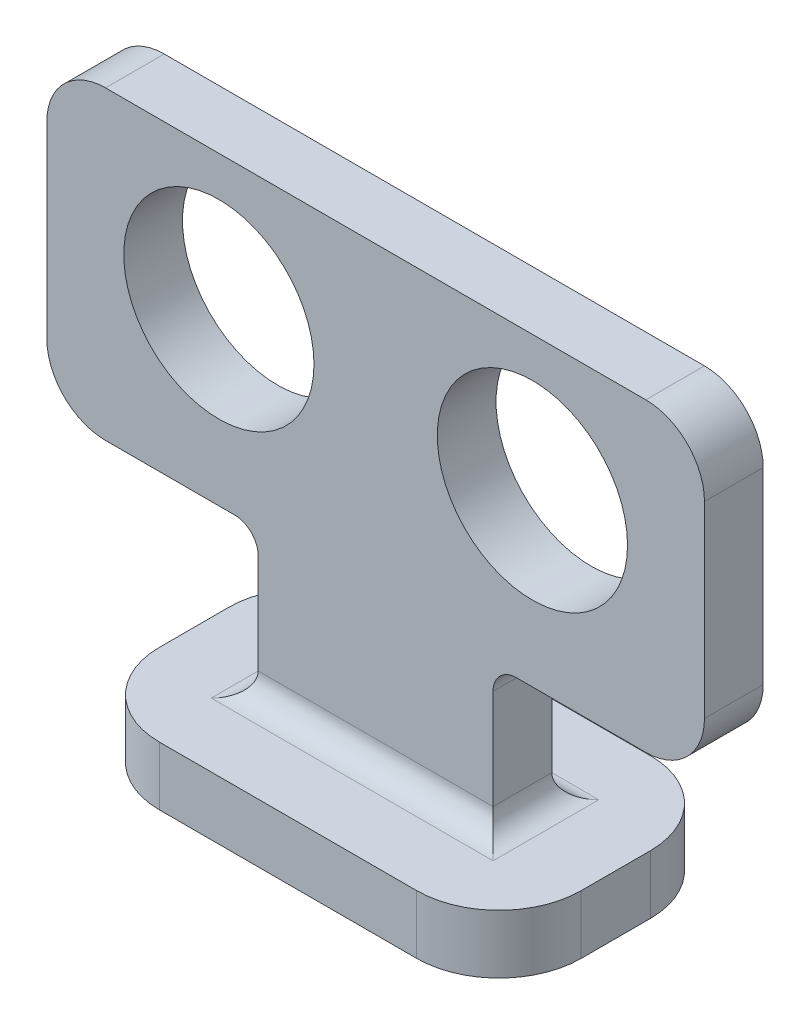
SolidWorks part; units mm, degrees
ref_plane "Alzado" through (0, 0, 0) normal (0, 0, 1) x (1, 0, 0)
ref_plane "Planta" through (0, 0, 0) normal (0, 1, 0) x (1, 0, 0)
ref_plane "Vista lateral" through (0, 0, 0) normal (1, 0, 0) x (0, 0, -1)
sketch "Sketch1" plane through (0, 0, 0) normal (0, 0, 1) x (1, 0, 0)
  line L0 (0, 11.5) -> (50, 11.5) construction
  line L1 (0, 0) -> (50, 0)
  line L2 (0, 0) -> (0, 23)
  line L3 (0, 23) -> (50, 23)
  line L4 (50, 0) -> (50, 23)
  line L6 (0, 23) -> (-3, 23)
  line L7 (0, 23) -> (0, 0)
  line L8 (0, 0) -> (-3, 0)
  line L9 (-3, 23) -> (-3, 0)
  line L10 (50, 23) -> (53, 23)
  line L11 (50, 23) -> (50, 0)
  line L12 (50, 0) -> (53, 0)
  line L13 (53, 23) -> (53, 0)
  line L14 (-3, 0) -> (53, 0)
  line L15 (-3, 0) -> (-3, -3)
  line L16 (-3, -3) -> (53, -3)
  line L17 (53, 0) -> (53, -3)
  circle A0 centre (11.65, 11.5) radius 8.1
  circle A1 centre (38.35, 11.5) radius 8.1
  dimension "D2" = 16.2
  dimension "D1" = 50
  dimension "D3" = 23
  dimension "D4" = 26.7
  dimension "D5" = 11.65
  dimension "D6" = 3
  dimension "D7" = 3
  dimension "D8" = 3
extrude "Boss-Extrude1" add sketch "Sketch1" along normal blind 5 contours L0 L2 L1 L4 A1 A0 | L7 L0 A0 A1 L11 L3 | L6 L9 L8 L2 L7 | L13 L10 L11 L4 L12 | L15 L14 L17 L16
sketch "Sketch7" plane through (0, -3, 0) normal (0, -1, 0) x (1, 0, 0)
  line L1 (-3, 5) -> (53, 5) construction
  line L5 (15, 0) -> (35, 0)
  line L6 (15, 0) -> (15, 5)
  line L7 (15, 5) -> (35, 5)
  line L8 (35, 0) -> (35, 5)
  point P10 (25, 2.5)
  dimension "D1" = 20
extrude "Boss-Extrude7" add sketch "Sketch7" along normal blind 12.5
sketch "Sketch8" plane through (0, -15.5, 0) normal (0, -1, 0) x (1, 0, 0)
  line L0 (15, 2.5) -> (35, 2.5) construction
  line L1 (15, 5) -> (15, 0) construction
  line L2 (35, 0) -> (35, 5) construction
  line L4 (7.05, -7.45) -> (42.95, -7.45)
  line L5 (7.05, -7.45) -> (7.05, 12.45)
  line L6 (7.05, 12.45) -> (42.95, 12.45)
  line L7 (42.95, -7.45) -> (42.95, 12.45)
  line L8 (7.05, -7.45) -> (42.95, 12.45) construction
  line L9 (7.05, 12.45) -> (42.95, -7.45) construction
  point P6 (25, 2.5)
  dimension "D1" = 19.9
  dimension "D2" = 35.9
extrude "Boss-Extrude8" add sketch "Sketch8" along normal blind 5
fillet "Fillet3" radius 5 4 edges at (53, -3, 2.5) (53, 23, 2.5) (-3, 23, 2.5) (-3, -3, 2.5)
fillet "Fillet5" radius 2 2 edges at (35, -3, 2.5) (15, -3, 2.5)
fillet "Fillet9" radius 2 4 edges at (15, -15.5, 2.5) (25, -15.5, 0) (25, -15.5, 5) (35, -15.5, 2.5)
fillet "Fillet10" radius 7 4 edges at (7.05, -18, -7.45) (7.05, -18, 12.45) (42.95, -18, -7.45) (42.95, -18, 12.45)
